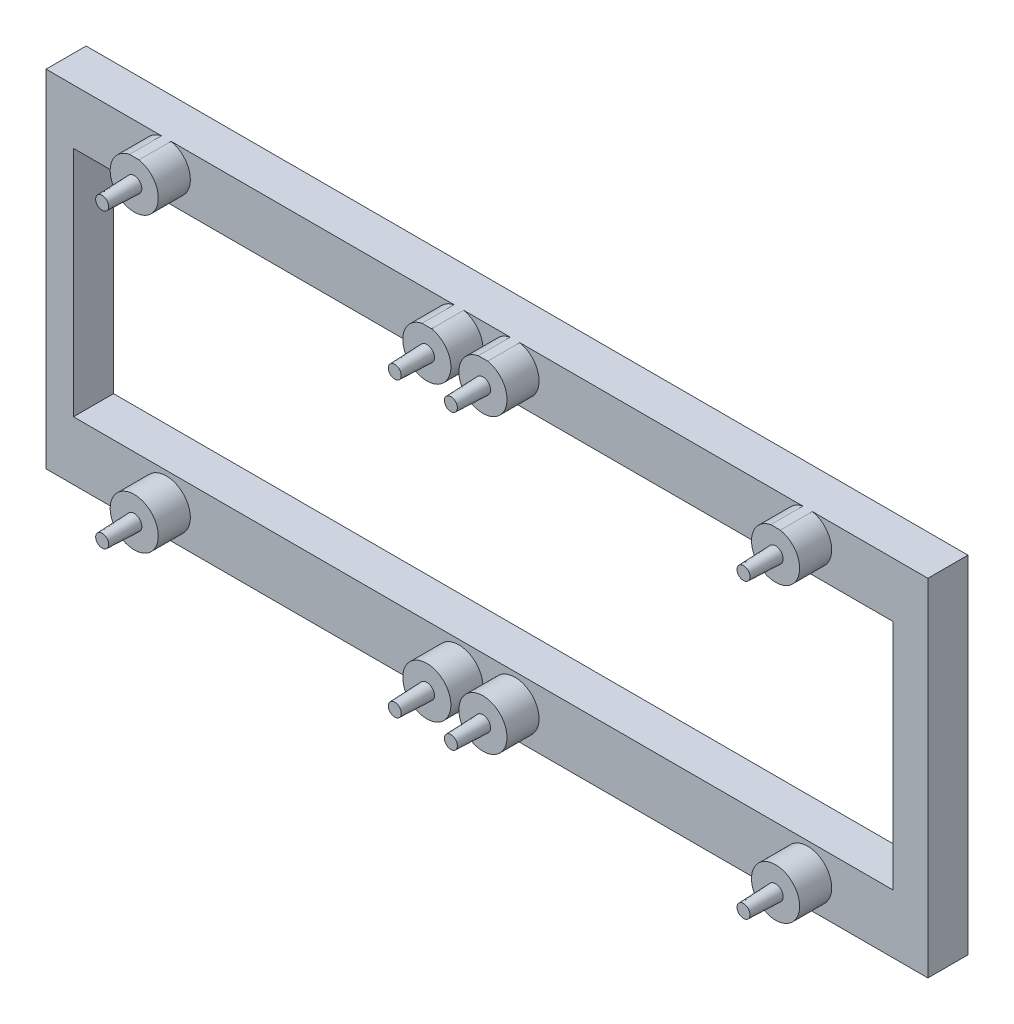
SolidWorks part; units mm, degrees
ref_plane "Ebene vorne" through (0, 0, 0) normal (0, 0, 1) x (1, 0, 0)
ref_plane "Ebene oben" through (0, 0, 0) normal (0, 1, 0) x (1, 0, 0)
ref_plane "Ebene rechts" through (0, 0, 0) normal (1, 0, 0) x (0, 0, -1)
sketch "Skizze1" plane through (0, 0, 0) normal (0, 0, 1) x (1, 0, 0)
  line L1 (-55, -85) -> (55, -85)
  line L2 (-55, -85) -> (-55, 85)
  line L3 (-55, 85) -> (55, 85)
  line L4 (55, -85) -> (55, 85)
  line L5 (-55, -85) -> (55, 85) construction
  line L6 (-55, 85) -> (55, -85) construction
  point P0 (0, 0)
  dimension "D1" = 110
  dimension "D2" = 170
extrude "Aufsatz-Linear austragen1" add sketch "Skizze1" along normal blind 5
fillet "Verrundung1" radius 5 4 edges at (-55, -85, 2.5) (55, -85, 2.5) (55, 85, 2.5) (-55, 85, 2.5)
sketch "Skizze7" plane through (0, 0, 5) normal (0, 0, 1) x (1, 0, 0)
  line L0 (-55, 80) -> (-55, -80) construction
  line L1 (-55, 73) -> (-43, 73)
  line L2 (-55, 73) -> (-55, 57)
  line L3 (-55, 57) -> (-43, 57)
  line L4 (-43, 73) -> (-43, 57)
  line L5 (50, 85) -> (-50, 85) construction
  line L18 (0, 85) -> (0, -85) construction
  line L19 (-50, -85) -> (50, -85) construction
  line L20 (-55, 0) -> (55, 0) construction
  line L21 (55, -80) -> (55, 80) construction
  line L22 (43, 73) -> (43, 57)
  line L23 (55, 57) -> (43, 57)
  line L24 (55, 73) -> (55, 57)
  line L25 (55, 73) -> (43, 73)
  line L26 (55, -73) -> (43, -73)
  line L27 (55, -73) -> (55, -57)
  line L28 (55, -57) -> (43, -57)
  line L29 (43, -73) -> (43, -57)
  line L30 (-43, -73) -> (-43, -57)
  line L31 (-55, -57) -> (-43, -57)
  line L32 (-55, -73) -> (-55, -57)
  line L33 (-55, -73) -> (-43, -73)
  dimension "D1" = 12
  dimension "D2" = 16
  dimension "D3" = 12
extrude "Aufsatz-Linear austragen3" add sketch "Skizze7" along normal blind 28
fillet "Verrundung2" radius 2 12 edges at (-49, 73, 5) (-49, 57, 5) (-43, 65, 5) (-49, -57, 5) (-43, -65, 5) (-49, -73, 5) (49, -73, 5) (43, -65, 5) (49, -57, 5) (49, 57, 5) (43, 65, 5) (49, 73, 5)
sketch "Skizze8" plane through (0, 0, 33) normal (0, 0, 1) x (1, 0, 0)
  line L0 (-43, 73) -> (-55, 73) construction
  line L1 (-55, 73) -> (-55, 57) construction
  line L5 (-55, 31.954) -> (-55, -16.1316) construction
  line L8 (-55, 55) -> (-55, -55) construction
  circle A1 centre (-49, 67) radius 4.2
  dimension "D1" = 8.4
  dimension "D2" = 6
  dimension "D3" = 6
extrude "Schnitt-Linear austragen3" cut sketch "Skizze8" against normal through all
pattern_linear "Lineares Muster1" count 2 spacing 134 along (0, -1, 0) count 2 spacing 98 along (1, 0, 0) of "Schnitt-Linear austragen3"
sketch "Skizze9" plane through (0, 0, 5) normal (0, 0, 1) x (1, 0, 0)
  line L0 (0, 85) -> (0, -85) construction
  line L1 (-28, -77) -> (28, -77) construction
  line L2 (-28, -77) -> (-28, 12) construction
  line L3 (-28, 12) -> (28, 12) construction
  line L4 (28, -77) -> (28, 12) construction
  line L5 (-28, -77) -> (28, 12) construction
  line L6 (-28, 12) -> (28, -77) construction
  line L11 (50, 85) -> (-50, 85) construction
  line L12 (-50, -85) -> (50, -85) construction
  line L13 (-55, 55) -> (-55, -55) construction
  line L14 (-40, 15.5) -> (-3.5, 15.5) construction
  line L15 (-40, 15.5) -> (-40, 52) construction
  line L16 (-40, 52) -> (-3.5, 52) construction
  line L17 (-3.5, 15.5) -> (-3.5, 52) construction
  line L18 (-40, 15.5) -> (-3.5, 52) construction
  line L19 (-40, 52) -> (-3.5, 15.5) construction
  line L20 (40, 52) -> (3.5, 15.5) construction
  line L26 (40, 15.5) -> (3.5, 52) construction
  line L35 (3.5, 15.5) -> (3.5, 52) construction
  line L36 (40, 52) -> (3.5, 52) construction
  line L37 (40, 15.5) -> (40, 52) construction
  line L38 (40, 15.5) -> (3.5, 15.5) construction
  circle A0 centre (24.75, -73.75) radius 3
  circle A1 centre (24.75, -16.25) radius 3
  circle A2 centre (-24.75, -16.25) radius 3
  circle A3 centre (-24.75, -73.75) radius 3
  circle A16 centre (-3.5, 52) radius 3
  circle A17 centre (-40, 52) radius 3
  circle A18 centre (-40, 15.5) radius 3
  circle A19 centre (-3.5, 15.5) radius 3
  circle A20 centre (3.5, 15.5) radius 3
  circle A21 centre (40, 15.5) radius 3
  circle A22 centre (40, 52) radius 3
  circle A23 centre (3.5, 52) radius 3
  point P0 (0, 0)
  point P5 (0, -32.5)
  point P21 (-21.75, 33.75)
  point P36 (21.75, 33.75)
  dimension "D3" = 3.25
  dimension "D4" = 6
  dimension "D5" = 57.5
  dimension "D13" = 6
  dimension "D1" = 56
  dimension "D2" = 89
  dimension "D6" = 3.25
  dimension "D7" = 8
  dimension "D8" = 28
  dimension "D9" = 36.5
  dimension "D10" = 36.5
  dimension "D11" = 15
  dimension "D12" = 33
extrude "Aufsatz-Linear austragen4" add sketch "Skizze9" along normal blind 4
sketch "Skizze10" plane through (0, 0, 9) normal (0, 0, 1) x (1, 0, 0)
  line L0 (0, -85) -> (0, 85) construction
  line L1 (-50, -85) -> (50, -85) construction
  line L2 (50, 85) -> (-50, 85) construction
  circle A0 centre (24.75, -73.75) radius 0.95
  circle A1 centre (24.75, -16.25) radius 0.95
  circle A2 centre (-24.75, -16.25) radius 0.95
  circle A3 centre (-24.75, -73.75) radius 0.95
  circle A20 centre (3.5, 15.5) radius 0.95
  circle A21 centre (40, 15.5) radius 0.95
  circle A22 centre (40, 52) radius 0.95
  circle A23 centre (3.5, 52) radius 0.95
  circle A24 centre (-3.5, 52) radius 0.95
  circle A25 centre (-40, 52) radius 0.95
  circle A26 centre (-40, 15.5) radius 0.95
  circle A27 centre (-3.5, 15.5) radius 0.95
  dimension "D1" = 1.9
  dimension "D2" = 1.9
extrude "Aufsatz-Linear austragen5" add sketch "Skizze10" along normal blind 4 draft 2
chamfer "Fase1" distance 1.2 angle 45 4 edges at (-44.8, 67, 33) (-44.8, -67, 33) (53.2, -67, 33) (53.2, 67, 33)
sketch "Skizze11" plane through (0, 0, 5) normal (0, 0, 1) x (1, 0, 0)
  line L0 (0, 85) -> (0, -85) construction
  line L1 (-30, 59) -> (30, 59)
  line L2 (-30, 59) -> (-30, 79)
  line L3 (-30, 79) -> (30, 79)
  line L4 (30, 59) -> (30, 79)
  line L5 (-30, 59) -> (30, 79) construction
  line L6 (-30, 79) -> (30, 59) construction
  line L7 (50, 85) -> (-50, 85) construction
  line L8 (-50, -85) -> (50, -85) construction
  point P0 (0, 69)
  dimension "D1" = 60
  dimension "D2" = 20
  dimension "D3" = 6
extrude "Schnitt-Linear austragen4" cut sketch "Skizze11" against normal through all
sketch "Skizze12" plane through (0, 0, 33) normal (0, 0, 1) x (1, 0, 0)
  line L0 (-49, 73) -> (-49, 57) construction
  line L1 (-43, 73) -> (-55, 73) construction
  line L2 (-55, 57) -> (-43, 57) construction
  line L3 (-43, 67) -> (-55, 67) construction
  line L4 (-43, 57) -> (-43, 73) construction
  line L5 (-55, 73) -> (-55, 57) construction
  line L6 (0, 85) -> (0, -85) construction
  line L7 (50, 85) -> (-50, 85) construction
  line L8 (-50, -85) -> (50, -85) construction
  line L9 (-55, 0) -> (55, 0) construction
  line L10 (-55, 55) -> (-55, -55) construction
  line L11 (55, -55) -> (55, 55) construction
  circle A0 centre (-49, 59.5) radius 1.75
  circle A1 centre (49, 59.5) radius 1.75
  circle A2 centre (-49, -59.5) radius 1.75
  circle A3 centre (49, -59.5) radius 1.75
  dimension "D1" = 3.5
  dimension "D2" = 7.5
extrude "Aufsatz-Linear austragen6" add sketch "Skizze12" along normal blind 4 draft 2
sketch "Skizze13" plane through (0, 0, 0) normal (0, 0, -1) x (-1, 0, 0)
  line L0 (49, 71.2) -> (49, 62.8) construction
  line L1 (44.8, 67) -> (53.2, 67) construction
  line L2 (0, 85) -> (0, -85) construction
  line L3 (-50, 85) -> (50, 85) construction
  line L4 (50, -85) -> (-50, -85) construction
  line L5 (-55, 0) -> (55, 0) construction
  line L6 (-55, -80) -> (-55, 80) construction
  line L7 (55, 80) -> (55, -80) construction
  circle A0 centre (49, 67) radius 4.2 construction
  circle A1 centre (49, 59.5) radius 2
  circle A2 centre (-49, 59.5) radius 2
  circle A3 centre (-49, -59.5) radius 2
  circle A4 centre (49, -59.5) radius 2
  dimension "D1" = 4
  dimension "D2" = 7.5
extrude "Schnitt-Linear austragen5" cut sketch "Skizze13" against normal blind 4.5
sketch "Skizze15" plane through (0, 0, 5) normal (0, 0, 1) x (1, 0, 0)
  line L0 (55, -55) -> (55, 55) construction
  line L1 (48, -50) -> (40, -50)
  line L2 (48, -50) -> (48, 0)
  line L3 (48, 0) -> (40, 0)
  line L4 (40, -50) -> (40, 0)
  line L5 (-50, -85) -> (50, -85) construction
  line L6 (0, -85) -> (0, 85) construction
  line L7 (50, 85) -> (-50, 85) construction
  line L8 (-48, 0) -> (-40, 0)
  line L9 (-40, -50) -> (-40, 0)
  line L10 (-48, -50) -> (-40, -50)
  line L11 (-48, -50) -> (-48, 0)
  dimension "D1" = 50
  dimension "D2" = 8
  dimension "D3" = 7
  dimension "D4" = 35
extrude "Schnitt-Linear austragen6" cut sketch "Skizze15" against normal through all
fillet "Verrundung3" radius 1 8 edges at (48, 0, 2.5) (40, 0, 2.5) (48, -50, 2.5) (40, -50, 2.5) (-40, -50, 2.5) (-48, -50, 2.5) (-40, 0, 2.5) (-48, 0, 2.5)
sketch "Skizze16" plane through (0, 0, 5) normal (0, 0, 1) x (1, 0, 0)
  line L1 (-72.0241, 11.7597) -> (63.6234, 11.7597)
  line L2 (-72.0241, 11.7597) -> (-72.0241, -92.9025)
  line L3 (-72.0241, -92.9025) -> (63.6234, -92.9025)
  line L4 (63.6234, 11.7597) -> (63.6234, -92.9025)
  line L5 (-72.0241, 89.1963) -> (63.6234, 89.1963)
  line L6 (-72.0241, 89.1963) -> (-72.0241, 54.9409)
  line L7 (-72.0241, 54.9409) -> (63.6234, 54.9409)
  line L8 (63.6234, 89.1963) -> (63.6234, 54.9409)
  line L9 (-51.5774, 48.0964) -> (50.618, 48.0964)
  line L10 (-51.5774, 48.0964) -> (-51.5774, 19.0957)
  line L11 (-51.5774, 19.0957) -> (50.618, 19.0957)
  line L12 (50.618, 48.0964) -> (50.618, 19.0957)
extrude "Schnitt-Linear austragen7" cut sketch "Skizze16" against normal through all and the other way through all
